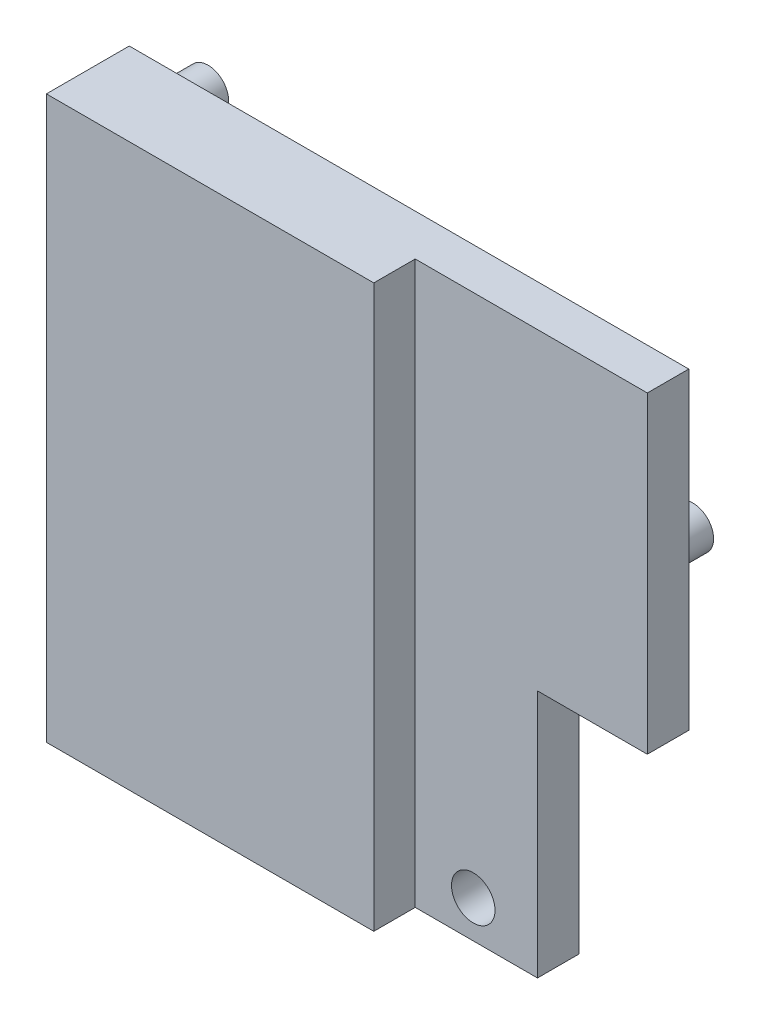
SolidWorks part; units mm, degrees
ref_plane "Front Plane" through (0, 0, 0) normal (0, 0, 1) x (1, 0, 0)
ref_plane "Top Plane" through (0, 0, 0) normal (0, 1, 0) x (1, 0, 0)
ref_plane "Right Plane" through (0, 0, 0) normal (1, 0, 0) x (0, 0, -1)
sketch "Sketch1" plane through (0, 0, 0) normal (0, 0, 1) x (1, 0, 0)
  line L0 (28.45, -32.1) -> (51.85, -32.1) construction
  line L1 (51.85, -38.7) -> (51.85, -32.1) construction
  line L2 (51.85, -32.1) -> (51.85, -55.5) construction
  line L3 (51.85, -55.5) -> (51.85, -57.3) construction
  line L4 (51.85, -57.3) -> (53.65, -57.3) construction
  line L5 (26.15, -30) -> (50.65, -30) construction
  line L6 (53.65, -57.3) -> (26.65, -57.3)
  line L7 (53.65, -57.3) -> (53.65, -30)
  line L8 (53.65, -30) -> (26.65, -30)
  line L9 (26.65, -57.3) -> (26.65, -30)
  line L10 (51.85, -55.5) -> (45.25, -55.5) construction
  circle A2 centre (45.25, -55.5) radius 1.05
  dimension "D5" = 6.6
  dimension "D7" = 2.1
  dimension "D1" = 23.4
  dimension "D2" = 1.8
  dimension "D3" = 1.8
  dimension "D4" = 27
extrude "Boss-Extrude1" add sketch "Sketch1" along normal blind 2
sketch "Sketch2" plane through (0, 0, 2) normal (0, 0, 1) x (1, 0, 0)
  line L1 (53.65, -57.3) -> (48.35, -57.3)
  line L2 (53.65, -57.3) -> (53.65, -45.3)
  line L3 (53.65, -45.3) -> (48.35, -45.3)
  line L4 (48.35, -57.3) -> (48.35, -45.3)
  dimension "D1" = 5.3
  dimension "D2" = 12
extrude "Cut-Extrude1" cut sketch "Sketch2" against normal through all
sketch "Sketch3" plane through (0, 0, 2) normal (0, 0, 1) x (1, 0, 0)
  circle A0 centre (28.45, -32.1) radius 1
  circle A1 centre (51.85, -38.7) radius 1
  dimension "D1" = 2
  dimension "D2" = 2
extrude "Boss-Extrude2" add sketch "Sketch3" against normal blind 4
sketch "Sketch4" plane through (0, 0, 2) normal (0, 0, 1) x (1, 0, 0)
  line L0 (26.65, -57.3) -> (48.35, -57.3) construction
  line L1 (26.65, -30) -> (42.45, -30)
  line L2 (26.65, -30) -> (26.65, -57.3)
  line L3 (26.65, -57.3) -> (42.45, -57.3)
  line L4 (42.45, -30) -> (42.45, -57.3)
  line L5 (53.65, -45.3) -> (53.65, -30) construction
  dimension "D1" = 11.2
extrude "Boss-Extrude3" add sketch "Sketch4" along normal blind 2
sketch "Sketch5" plane through (0, 0, 0) normal (0, 0, -1) x (-1, 0, 0)
  line L0 (-26.65, -30) -> (-26.65, -57.3) construction
  line L1 (-53.65, -30) -> (-26.65, -30)
  line L2 (-53.65, -30) -> (-53.65, -30.2)
  line L3 (-53.65, -30.2) -> (-26.65, -30.2)
  line L4 (-26.65, -30) -> (-26.65, -30.2)
  dimension "D1" = 0.2
extrude "Cut-Extrude2" cut sketch "Sketch5" against normal through all
